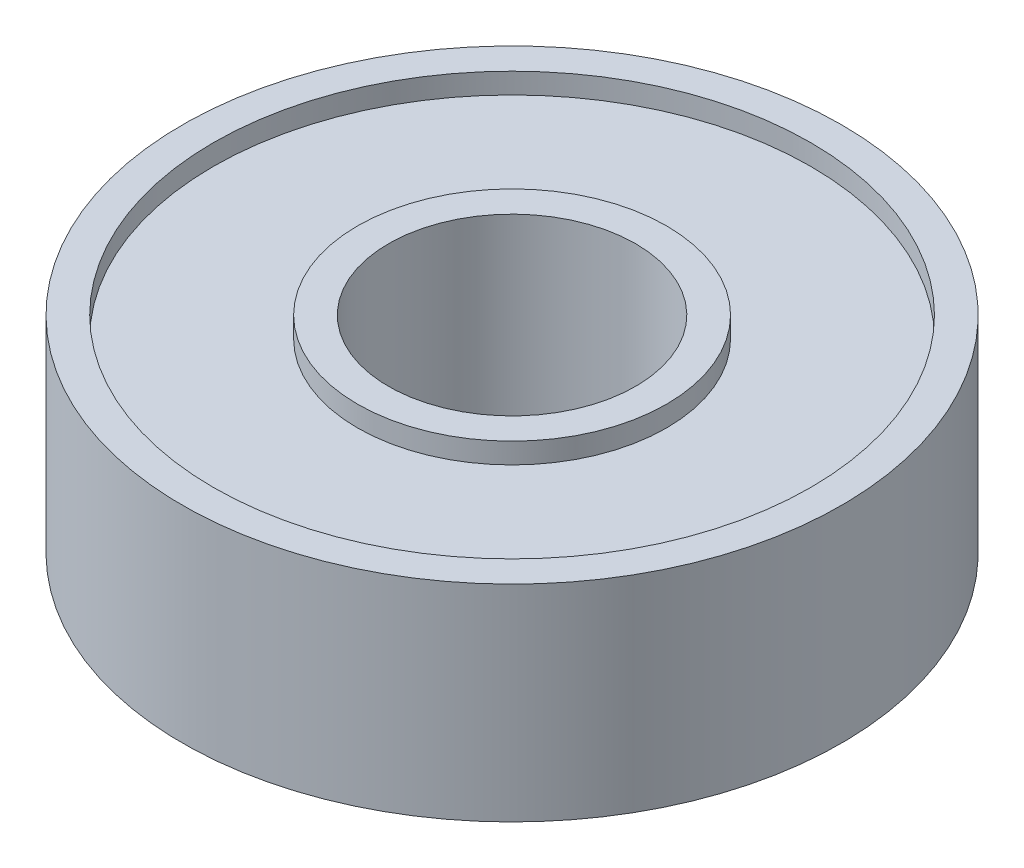
SolidWorks part; units mm, degrees
ref_plane "Alzado" through (0, 0, 0) normal (0, 0, 1) x (1, 0, 0)
ref_plane "Planta" through (0, 0, 0) normal (0, 1, 0) x (1, 0, 0)
ref_plane "Vista lateral" through (0, 0, 0) normal (1, 0, 0) x (0, 0, -1)
sketch "Croquis1" plane through (0, 0, 0) normal (0, 0, 1) x (1, 0, 0)
  line L0 (0, 0) -> (0, 16.452) construction
  line L1 (-6, 6.8567) -> (-6, 16.8567)
  line L2 (-6, 16.8567) -> (-7.5, 16.8567)
  line L3 (-7.5, 16.8567) -> (-7.5, 15.8567)
  line L4 (-7.5, 15.8567) -> (-14.5, 15.8567)
  line L5 (-14.5, 15.8567) -> (-14.5, 16.8567)
  line L6 (-14.5, 16.8567) -> (-16, 16.8567)
  line L7 (-16, 16.8567) -> (-16, 6.8567)
  line L8 (-16, 6.8567) -> (-14.5, 6.8567)
  line L9 (-14.5, 6.8567) -> (-14.5, 7.8567)
  line L10 (-14.5, 7.8567) -> (-7.5, 7.8567)
  line L11 (-7.5, 7.8567) -> (-7.5, 6.8567)
  line L12 (-7.5, 6.8567) -> (-6, 6.8567)
  dimension "D1" = 16
  dimension "D2" = 1.5
  dimension "D3" = 1
  dimension "D4" = 1
  dimension "D5" = 10
  dimension "D6" = 6
revolve "Revolución1" add sketch "Croquis1" angle 360 about L0
